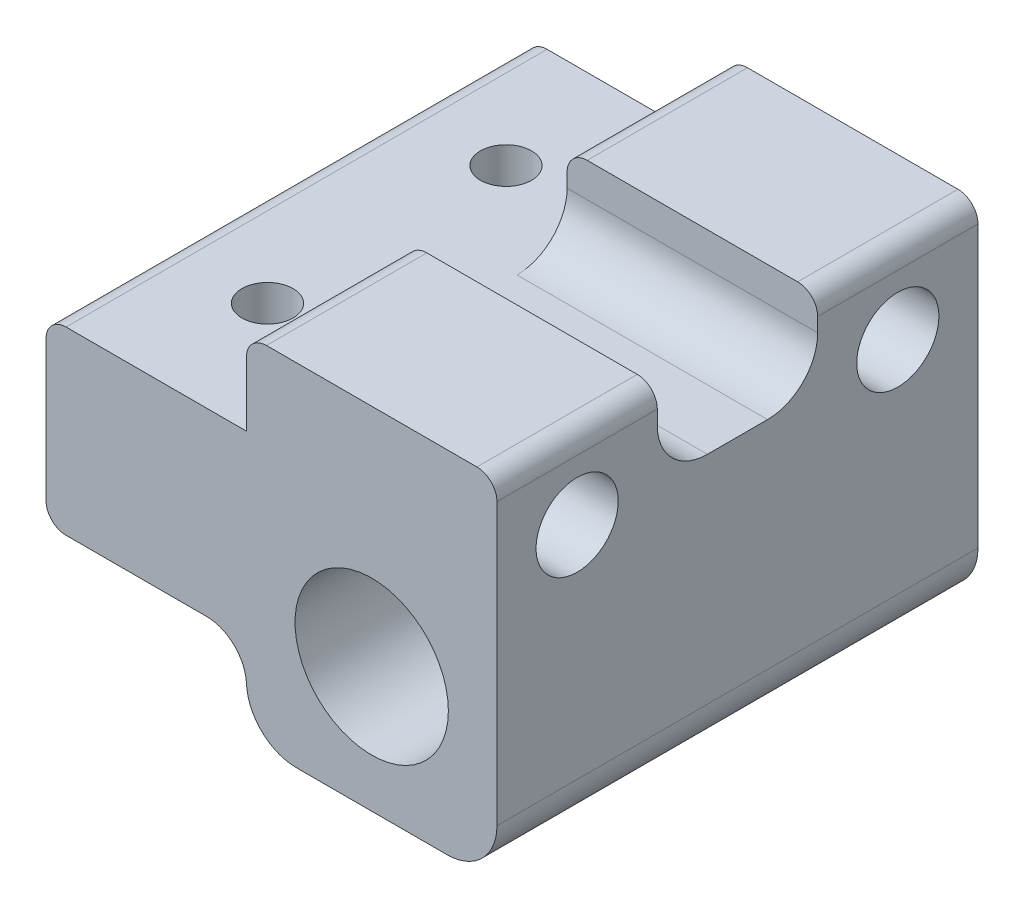
SolidWorks part; units mm, degrees
ref_plane "前视基准面" through (0, 0, 0) normal (0, 0, 1) x (1, 0, 0)
ref_plane "上视基准面" through (0, 0, 0) normal (0, 1, 0) x (1, 0, 0)
ref_plane "右视基准面" through (0, 0, 0) normal (1, 0, 0) x (0, 0, -1)
sketch "草图1" plane through (0, 0, 0) normal (0, 1, 0) x (1, 0, 0)
  line L1 (-16.4829, 29.6488) -> (8.5171, 29.6488)
  line L2 (-16.4829, 29.6488) -> (-16.4829, -18.3512)
  line L3 (-16.4829, -18.3512) -> (8.5171, -18.3512)
  line L4 (8.5171, 29.6488) -> (8.5171, -18.3512)
  dimension "D1" = 48
  dimension "D2" = 25
extrude "凸台-拉伸1" add sketch "草图1" along normal blind 25
sketch "草图2" plane through (0, 0, 18.3512) normal (0, 0, 1) x (1, 0, 0)
  circle A0 centre (-3.9829, 12.5) radius 7.65
  dimension "D1" = 15.3
extrude "切除-拉伸1" cut sketch "草图2" against normal through all
sketch "草图3" plane through (0, 25, 0) normal (0, 1, 0) x (1, 0, 0)
  line L4 (-16.4829, 29.6488) -> (-16.4829, -18.3512)
  line L5 (-16.4829, -18.3512) -> (8.5171, -18.3512)
  line L6 (8.5171, -18.3512) -> (8.5171, 29.6488)
  line L8 (-16.4829, 29.6488) -> (-16.4829, -18.3512)
  line L9 (-16.4829, -18.3512) -> (8.5171, -18.3512)
  line L12 (8.5171, -18.3512) -> (8.5171, 29.6488)
  line L14 (8.5171, 29.6488) -> (-16.4829, 29.6488)
  line L15 (8.5171, 29.6488) -> (-16.4829, 29.6488)
  dimension "D1" = 0
extrude "凸台-拉伸2" add sketch "草图3" along normal blind 10
sketch "草图4" plane through (8.5171, 0, 0) normal (1, 0, 0) x (0, 0, -1)
  line L0 (-18.3512, 35) -> (29.6488, 35) construction
  line L1 (29.6488, 35) -> (29.6488, 0) construction
  line L2 (-18.3512, 35) -> (-18.3512, 0) construction
  circle A0 centre (-10.3512, 27) radius 4.1
  circle A1 centre (21.6488, 27) radius 4.1
  dimension "D1" = 8.2
  dimension "D2" = 8.2
  dimension "D3" = 8
  dimension "D4" = 8
  dimension "D5" = 8
  dimension "D6" = 8
extrude "切除-拉伸2" cut sketch "草图4" against normal through all
ref_plane "基准面1" through (-16.4829, 0, 18.3512) normal (0, 0, 1) x (1, 0, 0)
fillet "圆角1" radius 5 2 edges at (-16.4829, 0, -5.6488) (8.5171, 0, -5.6488)
sketch "草图6" plane through (-16.4829, 0, 0) normal (-1, 0, 0) x (0, 0, 1)
  line L1 (18.3512, 8.5937) -> (18.3512, 26.5937)
  line L4 (-29.6488, 35) -> (-29.6488, 5)
  line L5 (-29.6488, 5) -> (18.3512, 5)
  line L6 (18.3512, 5) -> (18.3512, 35)
  line L7 (18.3512, 35) -> (-29.6488, 35)
  line L8 (-29.6488, 26.5937) -> (-29.6488, 8.5937)
  line L9 (-29.6488, 8.5937) -> (18.3512, 8.5937)
  line L11 (18.3512, 26.5937) -> (-29.6488, 26.5937)
  dimension "D2" = 18
  dimension "D1" = 0
extrude "凸台-拉伸3" add sketch "草图6" along normal blind 20
sketch "草图7" plane through (0, 8.5937, 0) normal (0, -1, 0) x (1, 0, 0)
  line L0 (8.5171, -17.5488) -> (-16.4829, -17.5488) construction
  line L1 (-16.4829, 6.2512) -> (8.5171, 6.2512) construction
  line L2 (-36.4829, -29.6488) -> (-36.4829, 18.3512) construction
  circle A0 centre (-26.4829, 6.2512) radius 2.55
  circle A1 centre (-26.4829, -17.5488) radius 2.55
  dimension "D1" = 5.1
  dimension "D2" = 5.1
  dimension "D3" = 0
  dimension "D4" = 0
  dimension "D5" = 10
  dimension "D6" = 10
extrude "切除-拉伸3" cut sketch "草图7" against normal through all
fillet "圆角3" radius 4 1 edges at (-16.4829, 8.5937, -5.6488)
sketch "草图8" plane through (0, 35, 0) normal (0, 1, 0) x (1, 0, 0)
  line L0 (-16.4829, 29.6488) -> (-16.4829, -18.3512) construction
  line L1 (-16.4829, 13.6488) -> (8.5171, 13.6488)
  line L2 (-16.4829, 13.6488) -> (-16.4829, -2.3512)
  line L3 (-16.4829, -2.3512) -> (8.5171, -2.3512)
  line L4 (8.5171, 13.6488) -> (8.5171, -2.3512)
  line L5 (8.5171, -18.3512) -> (8.5171, 29.6488) construction
  line L6 (8.5171, 29.6488) -> (-16.4829, 29.6488) construction
  dimension "D1" = 16
  dimension "D2" = 16
extrude "切除-拉伸4" cut sketch "草图8" against normal up to surface (8.4063 mm away) up to face at (-26.4829, 26.5937, 3.7012)
fillet "圆角4" radius 5 2 edges at (-3.9829, 26.5937, 2.3512) (-3.9829, 26.5937, -13.6488)
fillet "圆角5" radius 2 2 edges at (-36.4829, 8.5937, -5.6488) (-36.4829, 26.5937, -5.6488)
fillet "圆角6" radius 2 4 edges at (-16.4829, 35, -21.6488) (-16.4829, 35, 10.3512) (8.5171, 35, 10.3512) (8.5171, 35, -21.6488)
